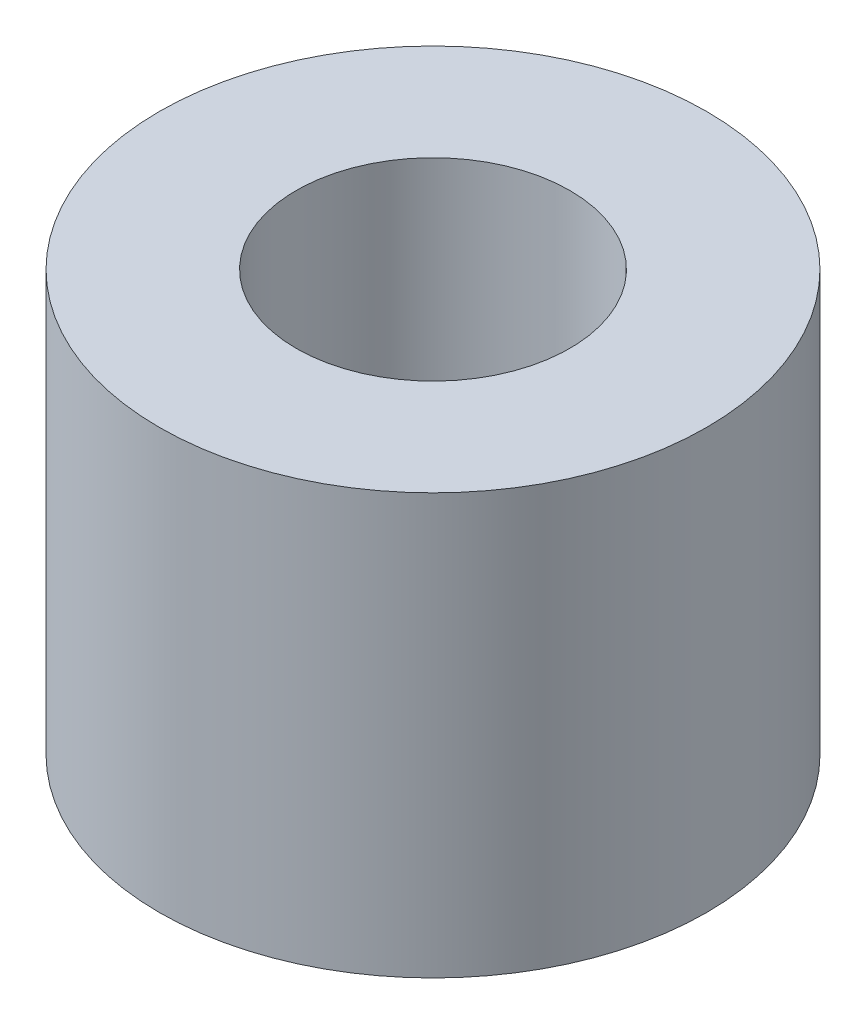
SolidWorks part; units mm, degrees
ref_plane "Front Plane" through (0, 0, 0) normal (0, 0, 1) x (1, 0, 0)
ref_plane "Top Plane" through (0, 0, 0) normal (0, 1, 0) x (1, 0, 0)
ref_plane "Right Plane" through (0, 0, 0) normal (1, 0, 0) x (0, 0, -1)
sketch "Sketch2" plane through (0, 0, 0) normal (0, 1, 0) x (1, 0, 0)
  circle A0 centre (0, 0) radius 6.35
  circle A1 centre (0, 0) radius 3.175
  dimension "D1" = 6.35
  dimension "D2" = 12.7
extrude "Boss-Extrude1" add sketch "Sketch2" along normal blind 9.75
